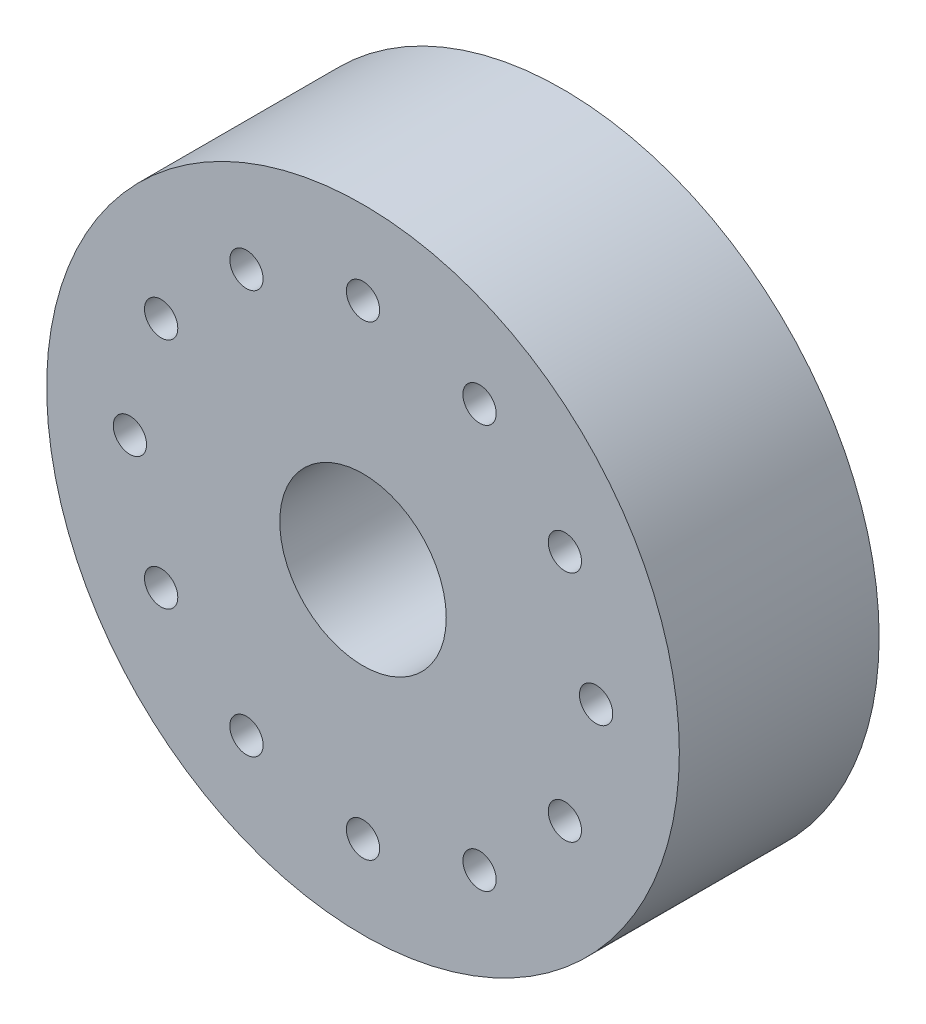
SolidWorks part; units mm, degrees
ref_plane "Plan de face" through (0, 0, 0) normal (0, 0, 1) x (1, 0, 0)
ref_plane "Plan de dessus" through (0, 0, 0) normal (0, 1, 0) x (1, 0, 0)
ref_plane "Plan de droite" through (0, 0, 0) normal (1, 0, 0) x (0, 0, -1)
sketch "Esquisse1" plane through (0, 0, 0) normal (0, 0, 1) x (1, 0, 0)
  circle A0 centre (0, 0) radius 9.5
  circle A1 centre (0, 0) radius 2.5
  circle A2 centre (0, 7) radius 0.5
  circle A3 centre (3.5, 6.0622) radius 0.5
  circle A4 centre (6.0622, 3.5) radius 0.5
  circle A5 centre (7, 0) radius 0.5
  circle A6 centre (6.0622, -3.5) radius 0.5
  circle A7 centre (3.5, -6.0622) radius 0.5
  circle A8 centre (0, -7) radius 0.5
  circle A9 centre (-3.5, -6.0622) radius 0.5
  circle A10 centre (-6.0622, -3.5) radius 0.5
  circle A11 centre (-7, 0) radius 0.5
  circle A12 centre (-6.0622, 3.5) radius 0.5
  circle A13 centre (-3.5, 6.0622) radius 0.5
  point P31 (0, 0)
  dimension "D1" = 19
  dimension "D2" = 5
  dimension "D3" = 1
  dimension "D4" = 7
  dimension "D5" = 12
extrude "Boss.-Extru.1" add sketch "Esquisse1" along normal blind 6
